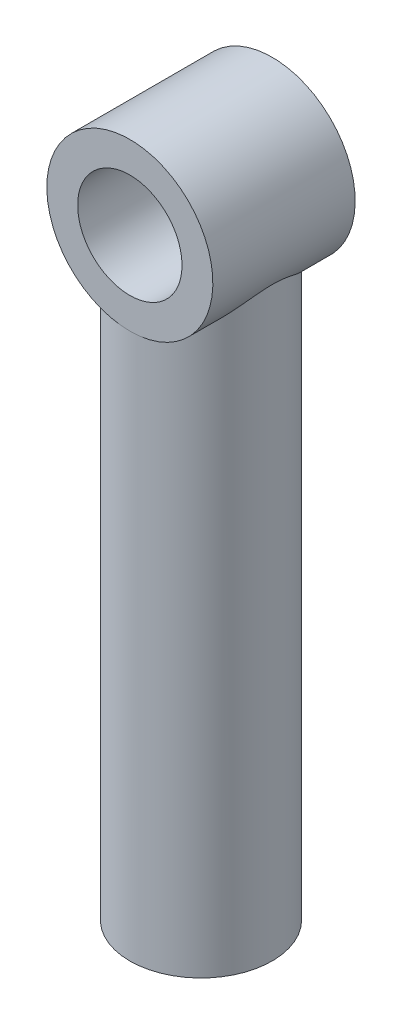
SolidWorks part; units mm, degrees
ref_plane "정면" through (0, 0, 0) normal (0, 0, 1) x (1, 0, 0)
ref_plane "윗면" through (0, 0, 0) normal (0, 1, 0) x (1, 0, 0)
ref_plane "우측면" through (0, 0, 0) normal (1, 0, 0) x (0, 0, -1)
sketch "스케치1" plane through (0, 0, 0) normal (0, 1, 0) x (1, 0, 0)
  circle A0 centre (0, 0) radius 15
  dimension "D1" = 30
extrude "보스-돌출1" add sketch "스케치1" along normal mid plane 130
sketch "스케치2" plane through (0, 0, 0) normal (0, 0, 1) x (1, 0, 0)
  line L0 (0, 0) -> (0, 67.5) construction
  line L2 (0, 67.5) -> (0, 85) construction
  line L3 (-15, -65) -> (15, -65) construction
  circle A0 centre (0, 67.5) radius 17.5
  circle A1 centre (0, 67.5) radius 11 construction
  dimension "D1" = 35
  dimension "D2" = 6.5
  dimension "D3" = 150
extrude "보스-돌출4" add sketch "스케치2" along normal mid plane 30
sketch "스케치3" plane through (0, 0, 0) normal (0, 0, 1) x (1, 0, 0)
  circle A0 centre (0, 67.5) radius 11
  circle A1 centre (0, 67.5) radius 17.5 construction
  dimension "D1" = 6.5
extrude "컷-돌출1" cut sketch "스케치3" against normal through all both and the other way through all
